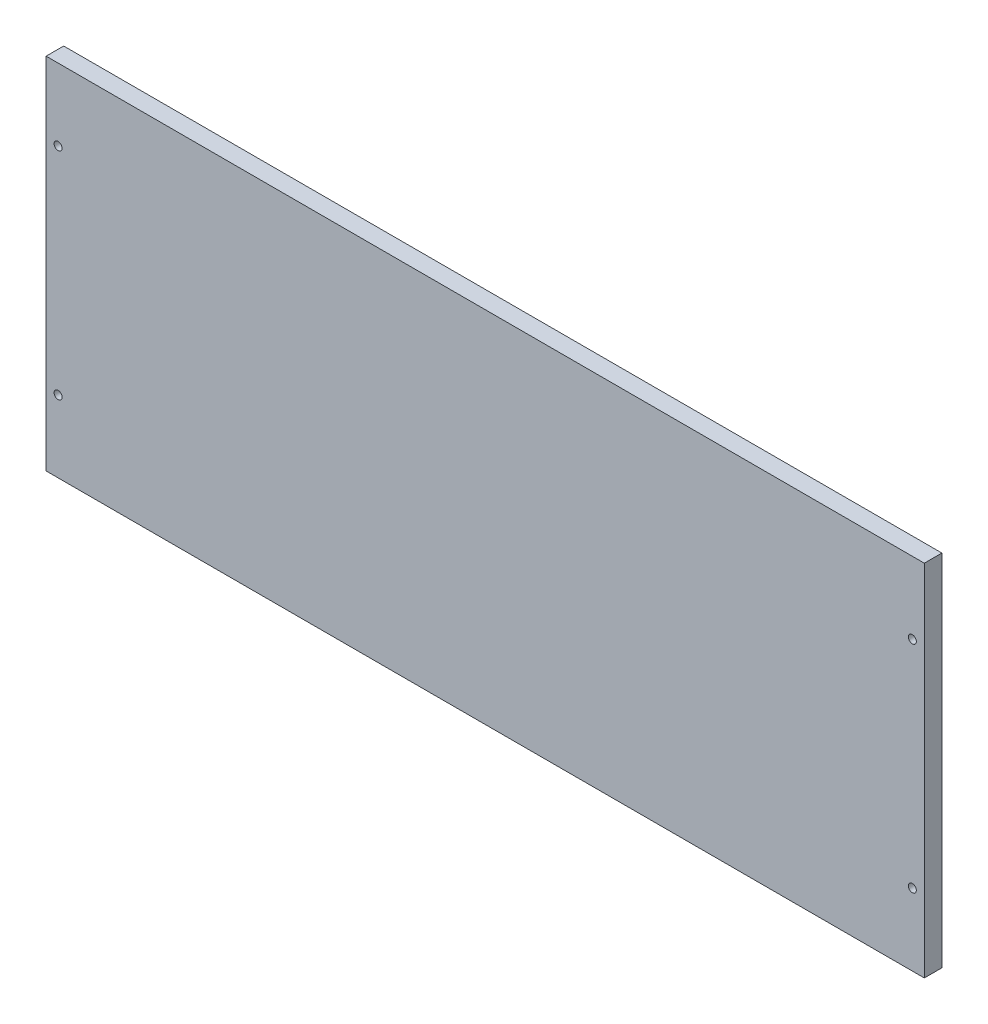
SolidWorks part; units mm, degrees
material "Pin"
ref_plane "Plan de face" through (0, 0, 0) normal (0, 0, 1) x (1, 0, 0)
ref_plane "Plan de dessus" through (0, 0, 0) normal (0, 1, 0) x (1, 0, 0)
ref_plane "Plan de droite" through (0, 0, 0) normal (1, 0, 0) x (0, 0, -1)
sketch "Esquisse1" plane through (0, 0, 0) normal (0, 0, 1) x (1, 0, 0)
  line L0 (550, 225) -> (-550, -225) construction
  line L1 (550, -225) -> (-550, -225)
  line L2 (550, -225) -> (550, 225)
  line L3 (550, 225) -> (-550, 225)
  line L4 (-550, -225) -> (-550, 225)
  point P4 (0, 225)
  point P5 (0, 0)
  dimension "D1" = 1100
  dimension "D2" = 450
extrude "Boss.-Extru.1" add sketch "Esquisse1" along normal blind 22
hole_wizard "Dégagement M81" positions "Esquisse2" profile "Esquisse3" hole size "M8" standard "ISO"
sketch "Esquisse2" plane through (360, -240, -30) normal (0, 0, -1) x (-1, 0, 0)
  point P0 (895, 375)
  point P4 (895, 105)
  point P7 (-175, 375)
  point P11 (-175, 105)
  point P14 (0, 0)
  point P15 (0, 0)
sketch "Esquisse3" plane through (-535, 135, -30) normal (1, 0, 0) x (0, 1, 0)
  line L0 (0, 0) -> (0, 123.0043)
  line L1 (0, 123.0043) -> (5, 120)
  line L2 (5, 120) -> (5, 0)
  line L3 (5, 0) -> (0, 0)
  line L4 (0, 123.0043) -> (-5, 120) construction
  line L5 (0, -6.35) -> (0, 107.95) construction
  dimension "Diamètre du perçage" = 10
  dimension "Profondeur du perçage" = 120
  dimension "Angle de pointe" = 118
